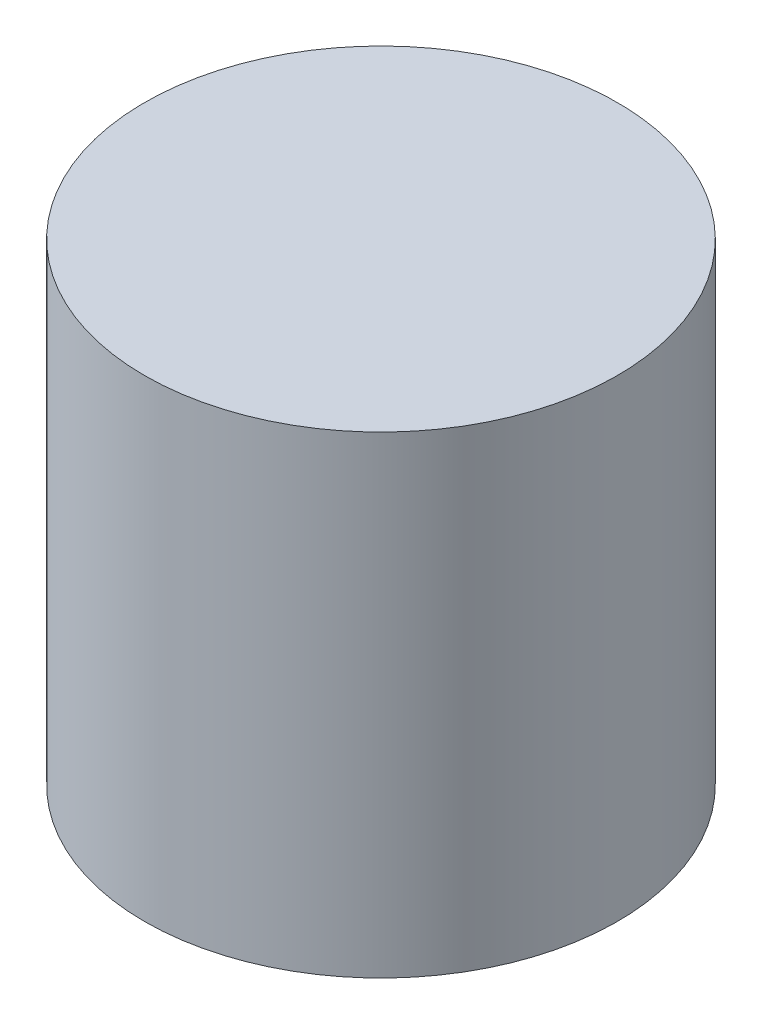
SolidWorks part; units mm, degrees
ref_plane "Front Plane" through (0, 0, 0) normal (0, 0, 1) x (1, 0, 0)
ref_plane "Top Plane" through (0, 0, 0) normal (0, 1, 0) x (1, 0, 0)
ref_plane "Right Plane" through (0, 0, 0) normal (1, 0, 0) x (0, 0, -1)
sketch "Sketch1" plane through (0, 0, 0) normal (0, 1, 0) x (1, 0, 0)
  circle A0 centre (0, 0) radius 0.925
  circle A1 centre (0, 0) radius 2
  dimension "D1" = 1.85
  dimension "D2" = 4
extrude "Boss-Extrude1" add sketch "Sketch1" along normal blind 3
sketch "Sketch2" plane through (0, 3, 0) normal (0, 1, 0) x (1, 0, 0)
  circle A0 centre (0, 0) radius 2
extrude "Boss-Extrude2" add sketch "Sketch2" along normal blind 1
